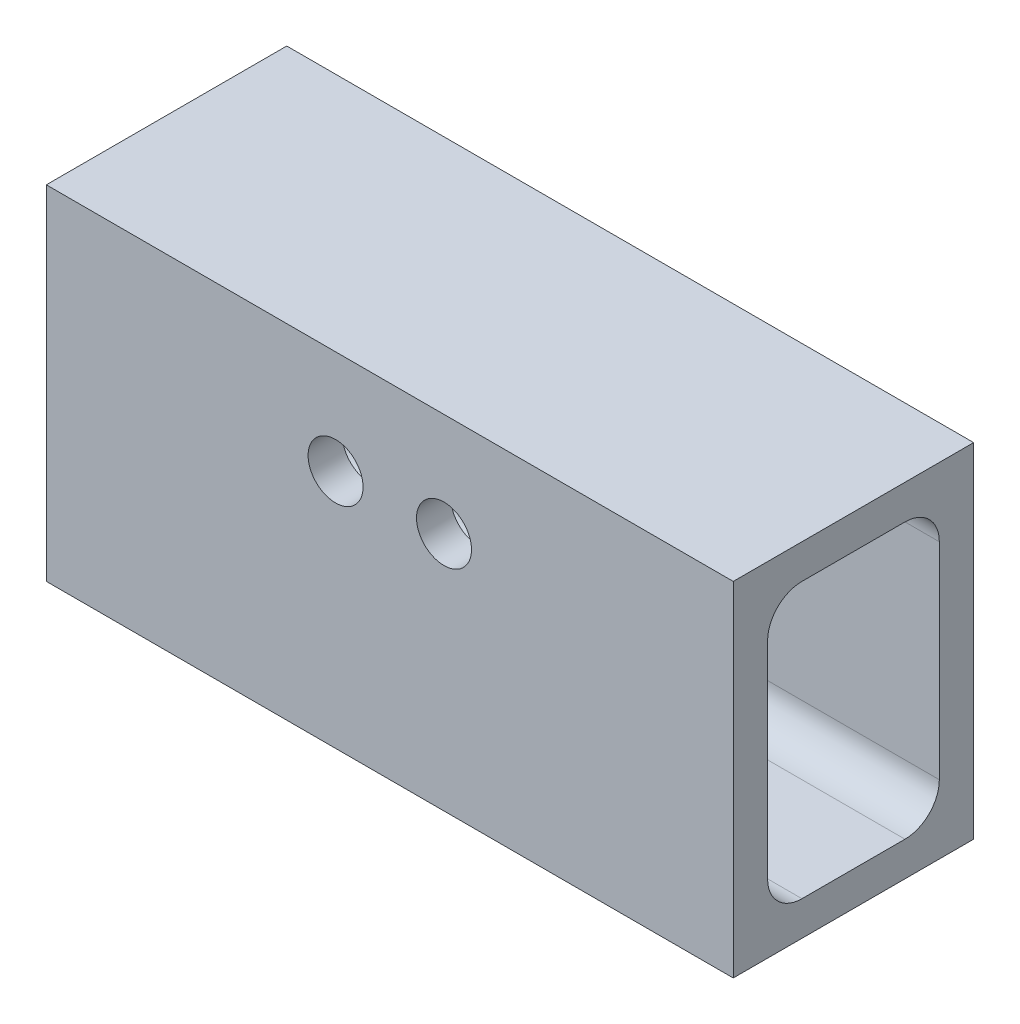
SolidWorks part; units mm, degrees
ref_plane "Front Plane" through (0, 0, 0) normal (0, 0, 1) x (1, 0, 0)
ref_plane "Top Plane" through (0, 0, 0) normal (0, 1, 0) x (1, 0, 0)
ref_plane "Right Plane" through (0, 0, 0) normal (1, 0, 0) x (0, 0, -1)
sketch "Sketch3" plane through (0, 0, 0) normal (0, 0, 1) x (1, 0, 0)
  line L1 (-47.6569, 27.3564) -> (52.3431, 27.3564)
  line L2 (-47.6569, 27.3564) -> (-47.6569, -22.6436)
  line L3 (-47.6569, -22.6436) -> (52.3431, -22.6436)
  line L4 (52.3431, 27.3564) -> (52.3431, -22.6436)
extrude "Boss-Extrude1" add sketch "Sketch3" along normal blind 35
sketch "Sketch4" plane through (-47.6569, 0, 0) normal (-1, 0, 0) x (0, 0, 1)
  line L6 (5, 22.3564) -> (30, 22.3564)
  line L10 (5, 22.3564) -> (5, -17.6436)
  line L12 (30, 22.3564) -> (30, -17.6436)
  line L14 (5, -17.6436) -> (30, -17.6436)
extrude "Cut-Extrude2" cut sketch "Sketch4" against normal blind 100
sketch "Sketch5" plane through (0, 0, 35) normal (0, 0, 1) x (1, 0, 0)
  circle A3 centre (-5.5504, 12.3036) radius 4.0023
  circle A4 centre (10.2366, 12.3036) radius 4.0023
extrude "Cut-Extrude4" cut sketch "Sketch5" against normal blind 5
fillet "Fillet2" radius 5 1 edges at (2.3431, 22.3564, 5)
fillet "Fillet3" radius 5 1 edges at (2.3431, 22.3564, 30)
fillet "Fillet4" radius 5 1 edges at (2.3431, -17.6436, 5)
fillet "Fillet5" radius 5 1 edges at (2.3431, -17.6436, 30)
scale "Scale1" bodies to scale 105 scale about centroid uniform scaling yes scale factor 0.15
